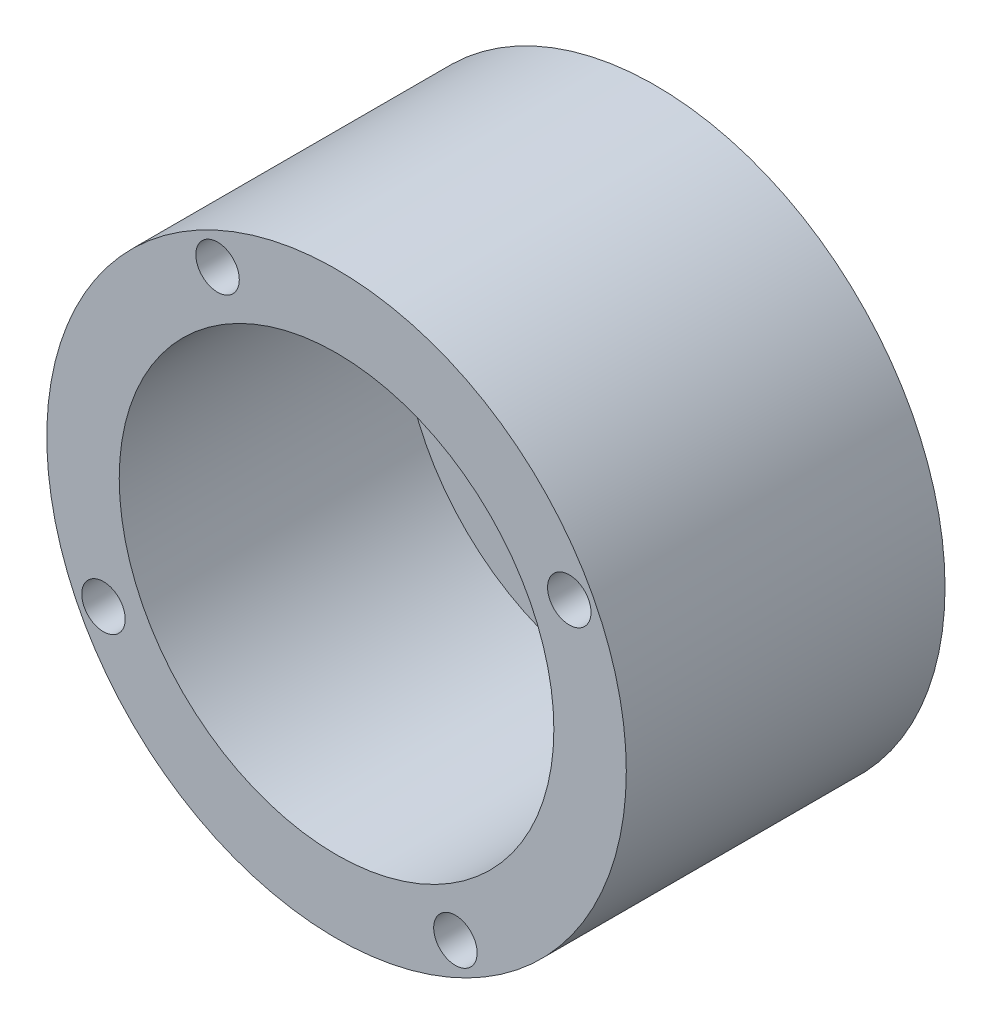
SolidWorks part; units mm, degrees
ref_plane "Plan de face" through (0, 0, 0) normal (0, 0, 1) x (1, 0, 0)
ref_plane "Plan de dessus" through (0, 0, 0) normal (0, 1, 0) x (1, 0, 0)
ref_plane "Plan de droite" through (0, 0, 0) normal (1, 0, 0) x (0, 0, -1)
sketch "Esquisse1" plane through (0, 0, 0) normal (0, 0, 1) x (1, 0, 0)
  line L0 (0, 1.1896) -> (0, -1.0883) construction
  line L1 (-1.6692, 0) -> (2.0606, 0) construction
  circle A0 centre (0, 0) radius 15
  circle A1 centre (0, 0) radius 20
  dimension "D1" = 5
  dimension "D2" = 30
extrude "Boss.-Extru.1" add sketch "Esquisse1" along normal blind 22
sketch "Esquisse5" plane through (0, 0, 0) normal (0, 0, -1) x (-1, 0, 0)
  circle A0 centre (0, 0) radius 15
  dimension "D1" = 30
extrude "Boss.-Extru.3" add sketch "Esquisse5" against normal blind 2.5
sketch "Esquisse12" plane through (0, 0, 0) normal (0, 0, -1) x (-1, 0, 0)
  circle A0 centre (0, 0) radius 4.25
  dimension "D1" = 8.5
extrude "Enlèv. mat.-Extru.2" cut sketch "Esquisse12" against normal blind 2.5
sketch "Esquisse13" plane through (0, 0, 22) normal (0, 0, 1) x (1, 0, 0)
  circle A0 centre (16.0656, 8.2735) radius 1.5
  circle A1 centre (8.2041, -16.0063) radius 1.5
  circle A2 centre (-16.0866, -8.2062) radius 1.5
  circle A3 centre (-8.2128, 16.0233) radius 1.5
  dimension "D1" = 3
  dimension "D2" = 3
  dimension "D3" = 3
  dimension "D4" = 3
extrude "Enlèv. mat.-Extru.3" cut sketch "Esquisse13" against normal blind 6
